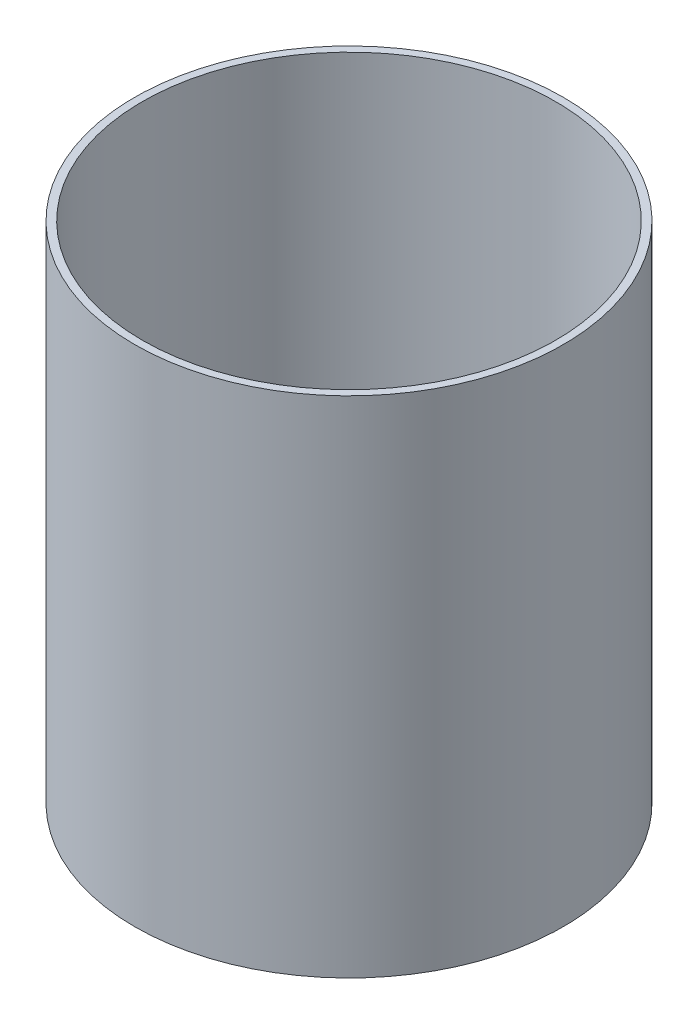
SolidWorks part; units mm, degrees
material "E-Glass Fiber"
ref_plane "Front Plane" through (0, 0, 0) normal (0, 0, 1) x (1, 0, 0)
ref_plane "Top Plane" through (0, 0, 0) normal (0, 1, 0) x (1, 0, 0)
ref_plane "Right Plane" through (0, 0, 0) normal (1, 0, 0) x (0, 0, -1)
sketch "Sketch1" plane through (0, 0, 0) normal (0, 1, 0) x (1, 0, 0)
  circle A2 centre (0, 0) radius 85
  circle A3 centre (0, 0) radius 82
  dimension "D1" = 3
extrude "Boss-Extrude1" add sketch "Sketch1" along normal blind 200 contours A3
